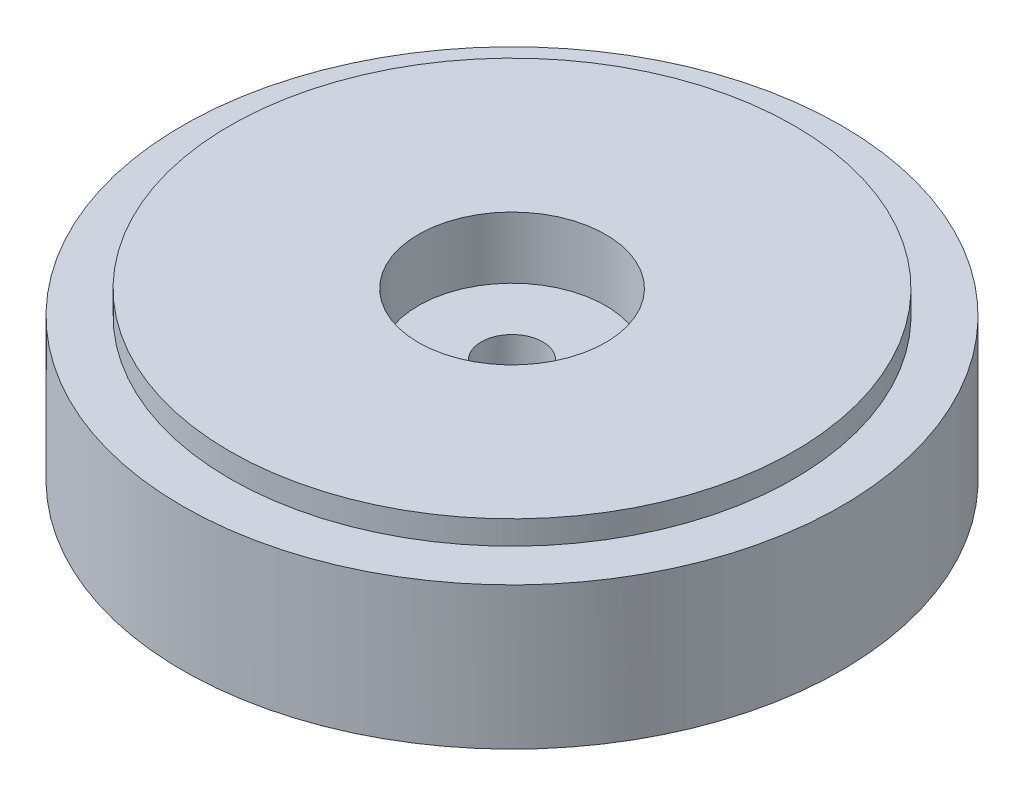
SolidWorks part; units mm, degrees
ref_plane "Front Plane" through (0, 0, 0) normal (0, 0, 1) x (1, 0, 0)
ref_plane "Top Plane" through (0, 0, 0) normal (0, 1, 0) x (1, 0, 0)
ref_plane "Right Plane" through (0, 0, 0) normal (1, 0, 0) x (0, 0, -1)
sketch "Sketch1" plane through (0, 0, 0) normal (0, 1, 0) x (1, 0, 0)
  circle A0 centre (0, 0) radius 69.5
  dimension "D1" = 139
extrude "Boss-Extrude1" add sketch "Sketch1" along normal blind 40
sketch "Sketch2" plane through (0, 40, 0) normal (0, 1, 0) x (1, 0, 0)
  circle A0 centre (0, 0) radius 69.5
  circle A1 centre (0, 0) radius 59.5
  dimension "D1" = 119
extrude "Cut-Extrude1" cut sketch "Sketch2" against normal blind 5 contours A0 | A1
sketch "Sketch3" plane through (0, 0, 0) normal (0, -1, 0) x (1, 0, 0)
  circle A0 centre (0, 0) radius 69.5
  circle A1 centre (0, 0) radius 59.5
  dimension "D1" = 119
extrude "Cut-Extrude2" cut sketch "Sketch3" against normal blind 5 contours A1 | A0
sketch "Sketch4" plane through (0, 40, 0) normal (0, 1, 0) x (1, 0, 0)
  circle A0 centre (0, 0) radius 19.75
  dimension "D1" = 39.5
extrude "Cut-Extrude4" cut sketch "Sketch4" against normal blind 13
sketch "Sketch5" plane through (0, 0, 0) normal (0, -1, 0) x (1, 0, 0)
  circle A0 centre (0, 0) radius 17
  dimension "D1" = 34
extrude "Boss-Extrude2" add sketch "Sketch5" along normal blind 8
sketch "Sketch6" plane through (0, -8, 0) normal (0, -1, 0) x (1, 0, 0)
  circle A0 centre (0, 0) radius 6.5
extrude "Cut-Extrude5" cut sketch "Sketch6" against normal through all
